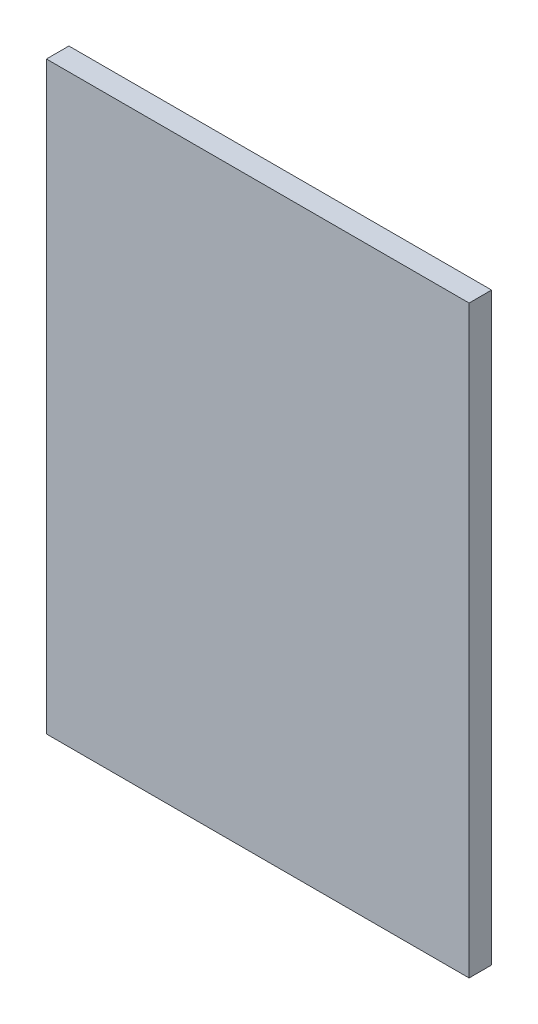
SolidWorks part; units mm, degrees
ref_plane "Front Plane" through (0, 0, 0) normal (0, 0, 1) x (1, 0, 0)
ref_plane "Top Plane" through (0, 0, 0) normal (0, 1, 0) x (1, 0, 0)
ref_plane "Right Plane" through (0, 0, 0) normal (1, 0, 0) x (0, 0, -1)
sketch "Sketch4" plane through (-106.4854, -33.902, 5) normal (0, 0, 1) x (-1, 0, 0)
  line L1 (-95.2552, -29.6318) -> (-1.2552, -29.6318)
  line L2 (-95.2552, -29.6318) -> (-95.2552, -159.6318)
  line L3 (-95.2552, -159.6318) -> (-1.2552, -159.6318)
  line L4 (-1.2552, -29.6318) -> (-1.2552, -159.6318)
  dimension "D1" = 94
  dimension "D2" = 130
extrude "Boss-Extrude2" add sketch "Sketch4" along normal blind 5
sketch "Sketch5" plane through (0, 0, 10) normal (0, 0, 1) x (1, 0, 0)
  line L0 (-23.6723, 2.451) -> (-23.6723, 10.3283)
  line L1 (-23.6723, 10.3283) -> (-15.189, 10.3283)
  line L2 (-15.189, 10.3283) -> (-15.189, 114.1475)
  line L3 (-15.189, 114.1475) -> (-26.702, 114.1475)
  line L4 (-26.702, 114.1475) -> (-26.702, 122.2269)
  line L5 (-26.702, 122.2269) -> (-91.1345, 122.2269)
  line L6 (-91.1345, 122.2269) -> (-91.1345, 114.1475)
  line L7 (-91.1345, 114.1475) -> (-100.6277, 114.1475)
  line L8 (-100.6277, 114.1475) -> (-100.6277, 11.5402)
  line L9 (-100.6277, 11.5402) -> (-89.1147, 11.5402)
